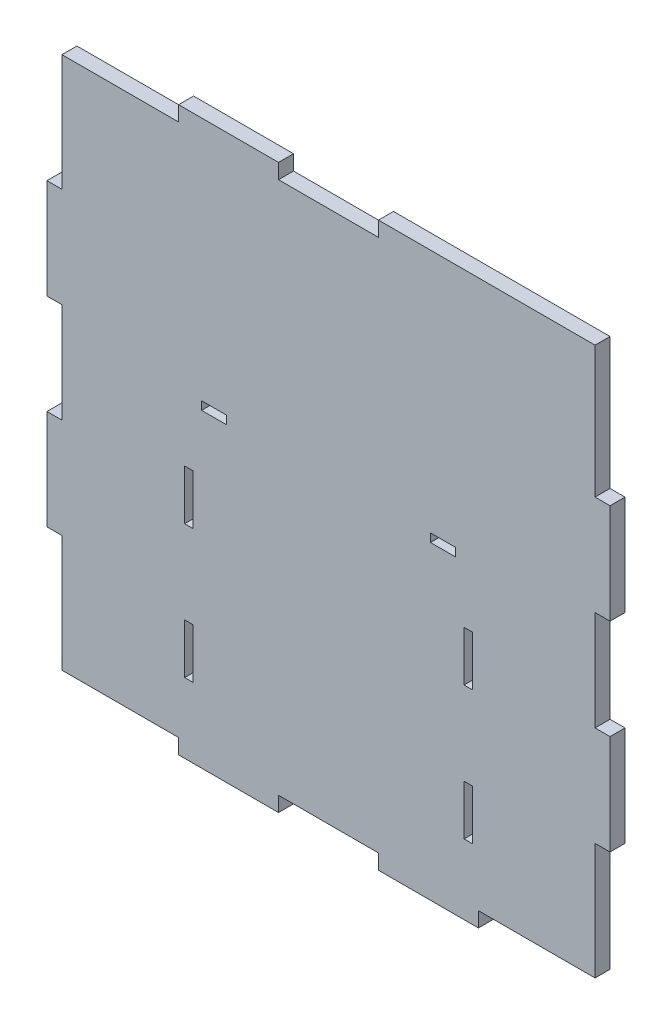
SolidWorks part; units mm, degrees
ref_plane "Front Plane" through (0, 0, 0) normal (0, 0, 1) x (1, 0, 0)
ref_plane "Top Plane" through (0, 0, 0) normal (0, 1, 0) x (1, 0, 0)
ref_plane "Right Plane" through (0, 0, 0) normal (1, 0, 0) x (0, 0, -1)
sketch "Sketch2" plane through (0, 0, 0) normal (0, 0, 1) x (1, 0, 0)
  line L2 (-160.0046, 60) -> (-160.0046, 0)
  line L4 (177.9954, 60) -> (177.9954, 0)
  line L5 (168.9954, 130) -> (168.9954, 60)
  line L7 (-151.0046, 130) -> (-151.0046, 60)
  line L8 (8.9954, 130) -> (8.9954, -190) construction
  line L9 (-81.0046, 139) -> (-81.0046, 130)
  line L10 (38.9954, 139) -> (38.9954, 130)
  line L11 (-21.0046, 139) -> (-21.0046, 130)
  line L13 (-151.2781, -30) -> (168.5573, -30) construction
  line L15 (38.9954, -199) -> (38.9954, -190)
  line L16 (-21.0046, -199) -> (-21.0046, -190)
  line L17 (-81.0046, -199) -> (-81.0046, -190)
  line L18 (-160.0046, 60) -> (-151.0046, 60)
  line L19 (-160.0046, -120) -> (-151.0046, -120)
  line L20 (-160.0046, 0) -> (-151.0046, 0)
  line L21 (-160.0046, -60) -> (-151.0046, -60)
  line L23 (-160.0046, 139) -> (-160.0046, -199) construction
  line L24 (-151.0046, 0) -> (-151.0046, -60)
  line L25 (-160.0046, -60) -> (-160.0046, -120)
  line L27 (-160.0046, 139) -> (177.9954, 139) construction
  line L30 (-151.0046, 130) -> (168.9954, 130) construction
  line L31 (-151.0046, 130) -> (-151.0046, -190) construction
  line L32 (-151.0046, -190) -> (168.9954, -190) construction
  line L35 (-160.0046, -199) -> (177.9954, -199) construction
  line L38 (168.9954, 60) -> (177.9954, 60)
  line L39 (-151.0046, -120) -> (-151.0046, -190)
  line L40 (177.9954, 0) -> (168.9954, 0)
  line L41 (177.9954, -60) -> (168.9954, -60)
  line L42 (168.9954, -120) -> (177.9954, -120)
  line L44 (177.9954, 139) -> (177.9954, -199) construction
  line L45 (168.9954, -120) -> (168.9954, -190)
  line L46 (168.9954, 130) -> (168.9954, -190) construction
  line L47 (177.9954, -60) -> (177.9954, -120)
  line L48 (168.9954, 0) -> (168.9954, -60)
  line L49 (-81.0046, 130) -> (-151.0046, 130)
  line L50 (-21.0046, 130) -> (38.9954, 130)
  line L51 (38.9954, 139) -> (98.9954, 139)
  line L53 (-21.0046, 139) -> (-81.0046, 139)
  line L54 (-21.0046, -199) -> (-81.0046, -199)
  line L55 (38.9954, -199) -> (98.9954, -199)
  line L56 (-21.0046, -190) -> (38.9954, -190)
  line L58 (-21.0046, -199) -> (-21.0046, -190)
  line L59 (38.9954, -199) -> (38.9954, -190)
  line L60 (-81.0046, -199) -> (-81.0046, -190)
  line L61 (-81.0046, -190) -> (-151.0046, -190)
  line L62 (98.9954, -190) -> (168.9954, -190)
  line L63 (98.9954, -190) -> (98.9954, -199)
  line L64 (-160.0046, 24.0866) -> (177.9954, 24.0866) construction
  line L65 (8.9954, 24.0866) -> (8.9954, 130) construction
  line L66 (98.9954, 139) -> (168.9954, 139)
  line L67 (168.9954, 139) -> (168.9954, 130)
  point P10 (-21.0046, 134.5)
  point P38 (-136.4053, -60)
  dimension "D1" = 30
  dimension "D2" = 320
  dimension "D4" = 60
  dimension "D5" = 30
  dimension "D6" = 60
  dimension "D7" = 320
  dimension "D8" = 60
  dimension "D11" = 9
  dimension "D12" = 9
  dimension "D13" = 9
  dimension "D14" = 60
  dimension "D15" = 60
  dimension "D16" = 160
  dimension "D17" = 30
  dimension "D3" = 9
extrude "Boss-Extrude1" add sketch "Sketch2" along normal blind 9
sketch "Sketch5" plane through (0, 0, 9) normal (0, 0, 1) x (1, 0, 0)
  line L1 (-72.1996, -190) -> (101.3035, -190) construction
  line L2 (90.3643, -127) -> (90.3643, -157)
  line L4 (95.3643, -127) -> (90.3643, -127)
  line L5 (95.3643, -157) -> (95.3643, -127)
  line L6 (93.9004, -195.6) -> (-71.5996, -195.6) construction
  line L7 (-71.5996, -195.6) -> (-77.1996, -195.6) construction
  line L9 (-77.1996, -14) -> (-72.1996, -14) construction
  line L10 (-77.1996, -14) -> (-77.1996, -9) construction
  line L11 (-77.1996, -9) -> (-42.1996, -9) construction
  line L12 (-42.1996, -9) -> (-42.1996, -14) construction
  line L13 (-151.0046, 0) -> (-151.0046, -60) construction
  line L14 (-42.1996, -14) -> (-72.1996, -14) construction
  line L15 (8.9954, -12.6217) -> (8.9954, -213.5239) construction
  line L32 (168.9954, 0) -> (168.9954, -60) construction
  line L49 (-151.0046, -120) -> (-151.0046, -190) construction
  line L50 (-21.0046, -190) -> (38.9954, -190) construction
  line L63 (-67.1996, -13) -> (-52.1996, -13)
  line L64 (-52.1996, -13) -> (-52.1996, -8)
  line L65 (-52.1996, -8) -> (-67.1996, -8)
  line L66 (-67.1996, -8) -> (-67.1996, -13)
  line L67 (-77.3736, -77) -> (-72.3736, -77)
  line L68 (-72.3736, -77) -> (-72.3736, -47)
  line L69 (-72.3736, -47) -> (-77.3736, -47)
  line L70 (-77.3736, -47) -> (-77.3736, -77)
  line L71 (-72.3736, -157) -> (-77.3736, -157)
  line L72 (-77.3736, -157) -> (-77.3736, -127)
  line L73 (-77.3736, -127) -> (-72.3736, -127)
  line L74 (-72.3736, -127) -> (-72.3736, -157)
  line L75 (90.3643, -157) -> (95.3643, -157)
  line L76 (95.3643, -47) -> (95.3643, -77)
  line L77 (90.3643, -47) -> (95.3643, -47)
  line L78 (90.3643, -77) -> (90.3643, -47)
  line L79 (95.3643, -77) -> (90.3643, -77)
  line L80 (85.1904, -8) -> (85.1904, -13)
  line L81 (70.1904, -13) -> (70.1904, -8)
  line L82 (85.1904, -13) -> (70.1904, -13)
  line L83 (70.1904, -8) -> (85.1904, -8)
  dimension "D2" = 177
  dimension "D3" = 35
  dimension "D4" = 177
  dimension "D5" = 5
  dimension "D6" = 113
  dimension "D7" = 33
  dimension "D9" = 320
  dimension "D10" = 160
  dimension "D13" = 82.4352
extrude "Cut-Extrude2" cut sketch "Sketch5" against normal blind 9
